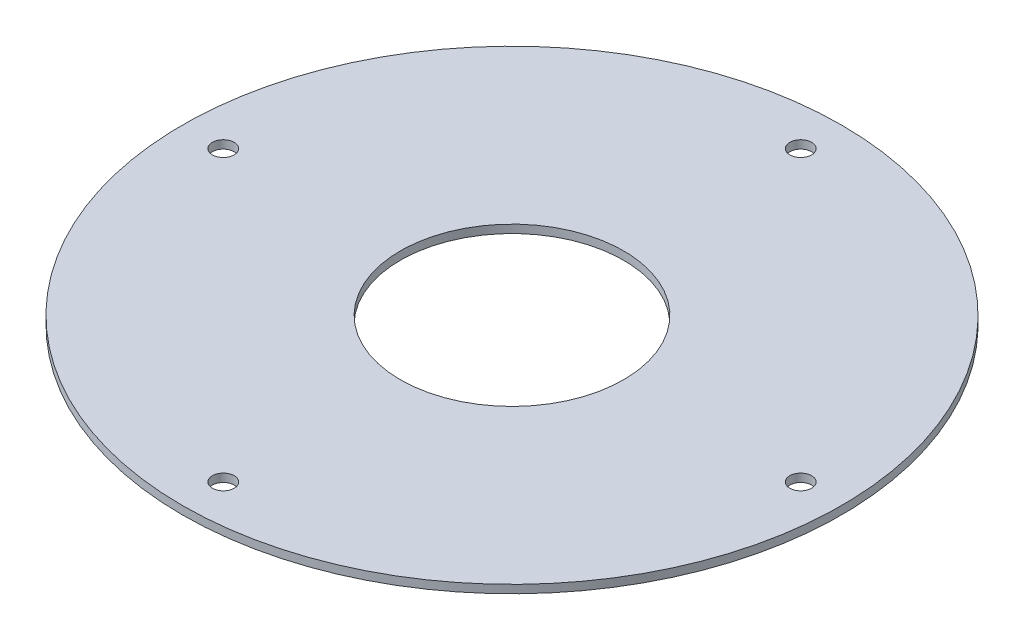
SolidWorks part; units mm, degrees
ref_plane "Front Plane" through (0, 0, 0) normal (0, 0, 1) x (1, 0, 0)
ref_plane "Top Plane" through (0, 0, 0) normal (0, 1, 0) x (1, 0, 0)
ref_plane "Right Plane" through (0, 0, 0) normal (1, 0, 0) x (0, 0, -1)
sketch "Sketch1" plane through (0, 0, 0) normal (0, 1, 0) x (1, 0, 0)
  circle A0 centre (0, 0) radius 60.5
  circle A1 centre (0, 0) radius 20.5
extrude "Boss-Extrude1" add sketch "Sketch1" along normal blind 1.5
sketch "Sketch2" plane through (0, 1.5, 0) normal (0, 1, 0) x (1, 0, 0)
  circle A0 centre (0, 53) radius 2
  circle A1 centre (53, 0) radius 2
  circle A2 centre (0, -53) radius 2
  circle A3 centre (-53, 0) radius 2
  point P12 (0, 0)
  dimension "D1" = 4
extrude "Cut-Extrude1" cut sketch "Sketch2" against normal through all
